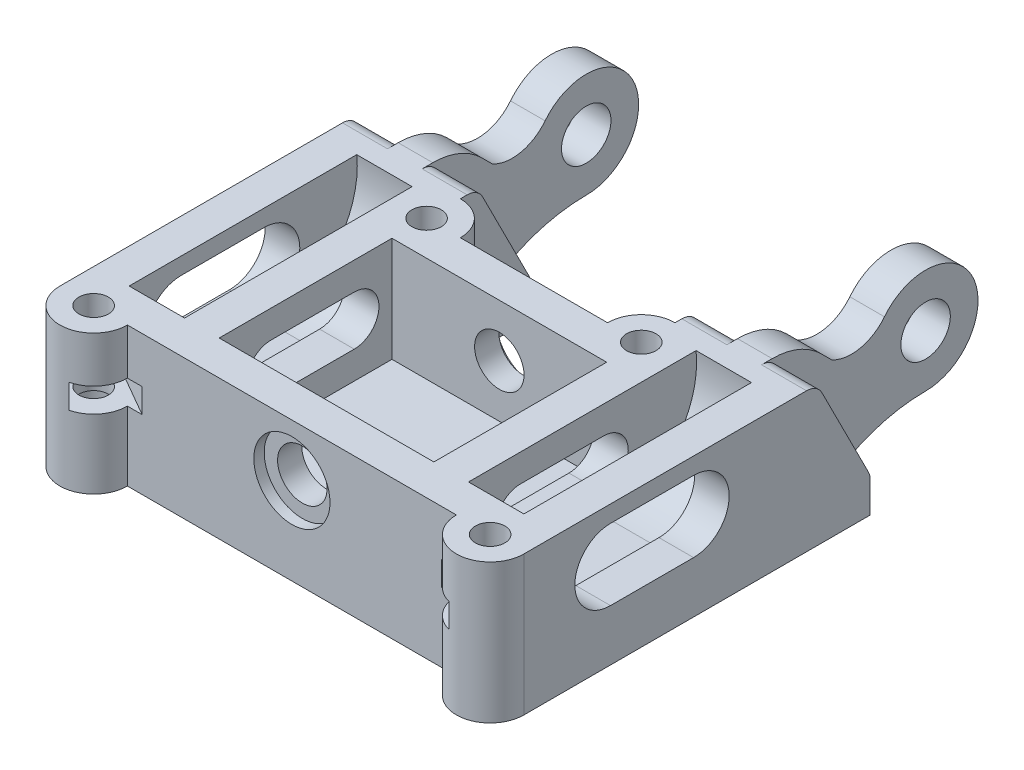
SolidWorks part; units mm, degrees
material "ABS"
ref_plane "Front Plane" through (0, 0, 0) normal (0, 0, 1) x (1, 0, 0)
ref_plane "Top Plane" through (0, 0, 0) normal (0, 1, 0) x (1, 0, 0)
ref_plane "Right Plane" through (0, 0, 0) normal (1, 0, 0) x (0, 0, -1)
sketch "Sketch1" plane through (0, 0, 0) normal (1, 0, 0) x (0, 0, -1)
  line L0 (0, 0) -> (-52, 0) construction
  line L1 (-52, 0) -> (-40, 0) construction
  line L2 (-52, 0) -> (-40, 0) construction
  line L3 (-52, 3.57) -> (-40, 3.57)
  line L4 (-52, -3.57) -> (-40, -3.57)
  line L7 (-14.5, -12.57) -> (-14.5, -7.57) construction
  line L14 (-64.5, -12.57) -> (-14.5, -12.57)
  line L18 (-13.5364, 3.0946) -> (-28.8864, 3.0946) construction
  line L19 (-13.5364, 3.0946) -> (-15.0829, 4.6411)
  line L20 (-24.4811, 7.57) -> (-22.1539, 7.57)
  line L23 (-64.5, 7.57) -> (-64.5, -12.57)
  line L24 (-64.5, 7.57) -> (-24.4811, 7.57)
  circle A0 centre (0, 0) radius 3.57
  arc A2 (-52, 3.57) -> (-52, -3.57) centre (-52, 0) ccw
  arc A3 (-40, -3.57) -> (-40, 3.57) centre (-40, 0) ccw
  arc A4 (-13.5364, 3.0946) -> (-5.9378, 4.6955) centre (-10.699, 8.4606) ccw
  arc A5 (0, -7.57) -> (-5.9378, 4.6955) centre (0, 0) ccw
  arc A6 (-14.5, -12.57) -> (0, -7.57) centre (0, -31.095) cw
  arc A10 (-22.1539, 7.57) -> (-15.0829, 4.6411) centre (-22.1539, -2.43) cw
  point P6 (-46, 0)
  point P22 (-22, 7.57)
  point P26 (-64.5, 7.57)
  dimension "D1" = 7.14
  dimension "D2" = 4
  dimension "D5" = 3.57
  dimension "D13" = 6.07
  dimension "D14" = 45
  dimension "D15" = 3.0946
  dimension "D16" = 10
  dimension "D3" = 52
  dimension "D4" = 12
  dimension "D10" = 50
  dimension "D11" = 5
extrude "Boss-Extrude1" add sketch "Sketch1" along normal blind 18
ref_plane "Plane1" through (9, 0, 0) normal (-1, 0, 0) x (0, 0, 1)
sketch "Sketch7" plane through (9, 0, 0) normal (-1, 0, 0) x (0, 0, 1)
  line L1 (68.6836, -7.57) -> (38.8542, -7.57)
  line L2 (68.6836, -7.57) -> (68.6836, 7.57)
  line L5 (64.5, -12.57) -> (14.5, -12.57) construction
  line L6 (26.6391, 7.57) -> (68.6836, 7.57)
  arc A0 (26.6391, 7.57) -> (38.8542, -7.57) centre (40.3166, 6.1075) ccw
  dimension "D1" = 5
extrude "Cut-Extrude4" cut sketch "Sketch7" against normal blind 4 and the other way blind 4
sketch "Sketch8" plane through (18, 0, 0) normal (1, 0, 0) x (0, 0, -1)
  line L35 (-26.5145, 0) -> (-3.762, 0) construction
  line L48 (-14.5, -12.57) -> (-14.5, -7.57)
  line L49 (-14.5, -7.57) -> (-22.1539, 7.57)
  line L50 (-14.5, -12.57) -> (7.3862, -6.3582)
  line L51 (7.3862, -6.3582) -> (9.4111, 3.26)
  line L52 (9.4111, 3.26) -> (4.2477, 15.2069)
  line L53 (4.2477, 15.2069) -> (-22.1539, 7.57)
  dimension "D1" = 0
  dimension "D2" = 5
extrude "Cut-Extrude5" cut sketch "Sketch8" against normal blind 6.5
sketch "Sketch9" plane through (0, 0, 0) normal (-1, 0, 0) x (0, 0, 1)
  line L0 (64.5, 7.57) -> (64.5, -12.57) construction
  line L1 (14.5, -12.57) -> (64.5, -12.57)
  line L2 (14.5, -12.57) -> (14.5, -7.57)
  line L3 (14.5, -7.57) -> (64.5, -7.57)
  line L4 (64.5, -12.57) -> (64.5, -7.57)
  dimension "D1" = 0
extrude "Boss-Extrude2" add sketch "Sketch9" along normal blind 15.5
mirror "Mirror2" about plane through (9, 0, 0) normal (-1, 0, 0) of "Cut-Extrude5"
fillet "Fillet8" radius 2.5 3 edges at (3.25, 7.57, 22.1539) (14.75, -7.57, 14.5) (14.75, 7.57, 22.1539)
sketch "Sketch13" plane through (18, 0, 0) normal (1, 0, 0) x (0, 0, -1)
  line L0 (-23.6914, 7.57) -> (-64.5, 7.57) construction
  line L1 (-64.5, -7.57) -> (-59.5, -7.57)
  line L2 (-64.5, -7.57) -> (-64.5, 7.57)
  line L3 (-64.5, 7.57) -> (-59.5, 7.57)
  line L4 (-59.5, -7.57) -> (-59.5, 7.57)
  dimension "D1" = 5
extrude "Boss-Extrude3" add sketch "Sketch13" against normal up to surface (33.5 mm away) up to face at (-15.5, -10.07, 39.5)
sketch "Sketch16" plane through (0, -7.57, 0) normal (0, 1, 0) x (1, 0, 0)
  line L0 (-15.5, -34.55) -> (50.0191, -34.55) construction
  line L1 (-15.5, -59.5) -> (-15.5, -14.5) construction
  line L2 (-15.5, -14.5) -> (0, -14.5) construction
  line L3 (0, -59.5) -> (0, -14.5) construction
  line L4 (-15.5, -34.55) -> (0, -34.55)
  line L5 (-15.5, -34.55) -> (-15.5, -29.55)
  line L6 (-15.5, -29.55) -> (0, -29.55)
  line L7 (0, -34.55) -> (0, -29.55)
  dimension "D1" = 20.05
  dimension "D2" = 5
extrude "Boss-Extrude4" add sketch "Sketch16" along normal up to surface (15.14 mm away) up to face at (9, 7.57, 43.0696)
sketch "Sketch14" plane through (0, 0, 64.5) normal (0, 0, 1) x (1, 0, 0)
  line L0 (-15.5, -12.57) -> (-15.5, 7.57) construction
  line L1 (-15.5, 3.57) -> (-15.5, -3.57)
  line L2 (18, 7.57) -> (-15.5, 7.57) construction
  arc A0 (-15.5, -3.57) -> (-15.5, 3.57) centre (-15.5, 0) ccw
  dimension "D1" = 7.14
  dimension "D2" = 7.57
extrude "Cut-Extrude8" cut sketch "Sketch14" against normal up to surface (34.95 mm away) up to face at (-7.75, 0, 29.55)
sketch "Sketch17" plane through (18, 0, 0) normal (1, 0, 0) x (0, 0, -1)
  line L0 (-40, 0) -> (-52, 0) construction
  line L1 (-40, -5.14) -> (-52, -5.14)
  line L2 (-40, 5.14) -> (-52, 5.14)
  arc A0 (-40, -5.14) -> (-40, 5.14) centre (-40, 0) ccw
  arc A1 (-52, 5.14) -> (-52, -5.14) centre (-52, 0) ccw
  point P4 (-46, 0)
  dimension "D1" = 5.14
extrude "Cut-Extrude9" cut sketch "Sketch17" against normal up to surface (5 mm away) up to face at (13, -0.6325, 45.3394)
sketch "Sketch19" plane through (0, 0, 64.5) normal (0, 0, 1) x (1, 0, 0)
  line L0 (-15.5, 5.5) -> (-15.5, -5.5)
  arc A0 (-15.5, -5.5) -> (-15.5, 5.5) centre (-15.5, 0) ccw
  dimension "D1" = 11
extrude "Cut-Extrude10" cut sketch "Sketch19" against normal blind 1.5
sketch "Sketch20" plane through (0, 0, 29.55) normal (0, 0, -1) x (-1, 0, 0)
  circle A1 centre (15.5, 0) radius 5.5
  dimension "D1" = 11
extrude "Cut-Extrude11" cut sketch "Sketch20" against normal blind 1.5
mirror "Mirror3" about plane through (-15.5, 0, 0) normal (1, 0, 0) of bodies 120 113
sketch "Sketch21" plane through (0, -7.57, 0) normal (0, 1, 0) x (1, 0, 0)
  line L1 (0, -14.5) -> (-31, -14.5)
  line L2 (0, -14.5) -> (0, -29.55)
  line L3 (0, -29.55) -> (-31, -29.55)
  line L4 (-31, -14.5) -> (-31, -29.55)
extrude "Cut-Extrude12" cut sketch "Sketch21" against normal up to surface (5 mm away) up to face at (-15.5, -12.57, 27)
sketch "Sketch30" plane through (0, 7.57, 0) normal (0, 1, 0) x (1, 0, 0)
  line L0 (0, -24.675) -> (0, -27.425)
  line L1 (18, -64.5) -> (-49, -64.5) construction
  line L2 (-2.125, -29.55) -> (-4.875, -29.55)
  line L3 (11, -64.5) -> (8.25, -64.5)
  line L4 (15.25, -64.5) -> (18, -64.5)
  line L5 (-15.5, -29.55) -> (-15.5, -64.5) construction
  line L6 (-31, -29.55) -> (0, -29.55) construction
  line L7 (-42, -64.5) -> (-39.25, -64.5)
  line L8 (-46.25, -64.5) -> (-49, -64.5)
  arc A0 (0, -27.425) -> (-2.125, -29.55) centre (0, -29.55) ccw
  arc A1 (0, -24.675) -> (-4.875, -29.55) centre (0, -29.55) ccw
  arc A2 (15.25, -64.5) -> (11, -64.5) centre (13.125, -64.5) cw
  arc A3 (18, -64.5) -> (8.25, -64.5) centre (13.125, -64.5) cw
  arc A4 (-46.25, -64.5) -> (-42, -64.5) centre (-44.125, -64.5) ccw
  arc A5 (-49, -64.5) -> (-39.25, -64.5) centre (-44.125, -64.5) ccw
  dimension "D1" = 4.25
  dimension "D2" = 4.875
  dimension "D3" = 2.125
  dimension "D4" = 4.875
extrude "Boss-Extrude11" add sketch "Sketch30" against normal up to surface (20.14 mm away) up to face at (-15.5, -12.57, 25.3417)
sketch "Sketch31" plane through (0, 7.57, 0) normal (0, 1, 0) x (1, 0, 0)
  line L0 (15.25, -64.5) -> (11, -64.5) construction
  line L1 (-42, -64.5) -> (-46.25, -64.5) construction
  circle A0 centre (0, -29.55) radius 2.125
  circle A1 centre (13.125, -64.5) radius 2.125
  circle A2 centre (-44.125, -64.5) radius 2.125
  dimension "D3" = 4.25
  dimension "D4" = 4.25
  dimension "D5" = 4.25
  dimension "D1" = 34.95
  dimension "D2" = 13.125
extrude "Cut-Extrude16" cut sketch "Sketch31" against normal up to surface (20.14 mm away) up to face at (-14.859, -12.57, 31.101)
ref_plane "Plane2" through (-15.5, 0, 0) normal (1, 0, 0) x (0, 0, -1)
mirror "Mirror4" about plane through (-15.5, 0, 0) normal (1, 0, 0) of "Cut-Extrude16", "Boss-Extrude11"
sketch "Sketch34" plane through (0, -12.57, 0) normal (0, -1, 0) x (1, 0, 0)
  circle A0 centre (-31, 29.55) radius 6.35
  arc A1 (-31, 24.675) -> (-26.125, 29.55) centre (-31, 29.55) ccw construction
  circle A2 centre (-44.125, 64.5) radius 6.35
  arc A3 (-39.25, 64.5) -> (-49, 64.5) centre (-44.125, 64.5) ccw construction
  circle A4 centre (13.125, 64.5) radius 6.35
  arc A5 (18, 64.5) -> (8.25, 64.5) centre (13.125, 64.5) ccw construction
  circle A6 centre (0, 29.55) radius 6.35
  arc A7 (-4.875, 29.55) -> (0, 24.675) centre (0, 29.55) ccw construction
  dimension "D1" = 12.7
ref_plane "Plane3" through (0, -2.57, 0) normal (0, -1, 0) x (-1, 0, 0)
sketch "Sketch32" plane through (0, -2.57, 0) normal (0, -1, 0) x (1, 0, 0)
  line L0 (-26.7605, 23.0609) -> (-23.2605, 29.123)
  line L1 (-31, 33.5915) -> (-34.5, 31.5707)
  line L2 (-34.5, 31.5707) -> (-34.5, 27.5293)
  line L3 (-34.5, 27.5293) -> (-26.7605, 23.0609)
  line L6 (-23.2605, 29.123) -> (-31, 33.5915)
  line L7 (-39.6166, 71.1444) -> (-47.625, 66.5207)
  line L8 (-47.625, 66.5207) -> (-47.625, 62.4793)
  line L9 (-47.625, 62.4793) -> (-44.125, 60.4585)
  line L10 (-44.125, 60.4585) -> (-36.1166, 65.0822)
  line L15 (4.5509, 65.4088) -> (13.125, 60.4585)
  line L16 (13.125, 60.4585) -> (16.625, 62.4793)
  line L17 (16.625, 62.4793) -> (16.625, 66.5207)
  line L18 (16.625, 66.5207) -> (8.0509, 71.471)
  line L19 (0, 33.5915) -> (-8.9319, 28.4346)
  line L22 (-5.4319, 22.3724) -> (3.5, 27.5293)
  line L23 (3.5, 27.5293) -> (3.5, 31.5707)
  line L24 (3.5, 31.5707) -> (0, 33.5915)
  line L25 (-29.25, 26.5189) -> (-27.5, 27.5293) [skipped]
  line L26 (-27.5, 29.55) -> (-27.5, 31.5707) [skipped]
  line L27 (-5.4319, 22.3724) -> (-8.9319, 28.4346)
  line L28 (-3.5, 27.5293) -> (-1.75, 26.5189) [skipped]
  line L29 (-3.5, 31.5707) -> (-3.5, 29.55) [skipped]
  line L30 (-36.1166, 65.0822) -> (-39.6166, 71.1444)
  line L31 (-42.375, 67.5311) -> (-44.125, 68.5415) [skipped]
  line L32 (-40.625, 64.5) -> (-40.625, 66.5207) [skipped]
  line L33 (4.5509, 65.4088) -> (8.0509, 71.471)
  line L34 (13.125, 68.5415) -> (11.375, 67.5311) [skipped]
  line L35 (9.625, 64.5) -> (9.625, 62.4793) [skipped]
  arc A0 (-29.25, 32.5811) -> (-32.75, 26.5189) centre (-31, 29.55) ccw construction
  arc A1 (-45.875, 67.5311) -> (-42.375, 61.4689) centre (-44.125, 64.5) ccw construction
  arc A2 (11.375, 61.4689) -> (14.875, 67.5311) centre (13.125, 64.5) ccw construction
  arc A3 (1.75, 26.5189) -> (-1.75, 32.5811) centre (0, 29.55) ccw construction
  dimension "D1" = 7
sketch "Sketch37" plane through (0, -12.57, 0) normal (0, -1, 0) x (1, 0, 0)
  line L12 (8.25, 64.5) -> (-39.25, 64.5)
  line L13 (-49, 64.5) -> (-49, 14.5)
  line L14 (-49, 14.5) -> (-42.5, 14.5)
  line L15 (-42.5, 14.5) -> (-37.5, 14.5)
  line L16 (-37.5, 14.5) -> (-31, 14.5)
  line L17 (-31, 14.5) -> (-31, 24.675)
  line L18 (-26.125, 29.55) -> (-4.875, 29.55)
  line L19 (0, 24.675) -> (0, 14.5)
  line L20 (0, 14.5) -> (6.5, 14.5)
  line L21 (6.5, 14.5) -> (11.5, 14.5)
  line L22 (11.5, 14.5) -> (18, 14.5)
  line L23 (18, 14.5) -> (18, 64.5)
  line L24 (8.25, 64.5) -> (-39.25, 64.5)
  line L25 (-49, 64.5) -> (-49, 14.5)
  line L26 (-49, 14.5) -> (-42.5, 14.5)
  line L27 (-42.5, 14.5) -> (-37.5, 14.5)
  line L28 (-37.5, 14.5) -> (-31, 14.5)
  line L29 (-31, 14.5) -> (-31, 24.675)
  line L30 (-26.125, 29.55) -> (-4.875, 29.55)
  line L31 (0, 24.675) -> (0, 14.5)
  line L32 (0, 14.5) -> (6.5, 14.5)
  line L33 (6.5, 14.5) -> (11.5, 14.5)
  line L34 (11.5, 14.5) -> (18, 14.5)
  line L35 (18, 14.5) -> (18, 64.5)
  arc A4 (18, 64.5) -> (8.25, 64.5) centre (13.125, 64.5) ccw
  arc A5 (-39.25, 64.5) -> (-49, 64.5) centre (-44.125, 64.5) ccw
  arc A6 (-31, 24.675) -> (-26.125, 29.55) centre (-31, 29.55) ccw
  arc A7 (-4.875, 29.55) -> (0, 24.675) centre (0, 29.55) ccw
  arc A8 (18, 64.5) -> (8.25, 64.5) centre (13.125, 64.5) ccw
  arc A9 (-39.25, 64.5) -> (-49, 64.5) centre (-44.125, 64.5) ccw
  arc A10 (-31, 24.675) -> (-26.125, 29.55) centre (-31, 29.55) ccw
  arc A11 (-4.875, 29.55) -> (0, 24.675) centre (0, 29.55) ccw
  dimension "D1" = 0
sketch "Sketch38" plane through (0, -12.57, 0) normal (0, -1, 0) x (1, 0, 0)
  circle A0 centre (-31, 29.55) radius 3
  circle A1 centre (0, 29.55) radius 3
  circle A2 centre (13.125, 64.5) radius 3
  circle A3 centre (-44.125, 64.5) radius 3
  dimension "D1" = 6
  dimension "D2" = 6
  dimension "D3" = 6
  dimension "D4" = 6
extrude "Cut-Extrude19" cut sketch "Sketch38" against normal blind 8
extrude "Cut-Extrude21" cut sketch "Sketch32" against normal blind 3.5
